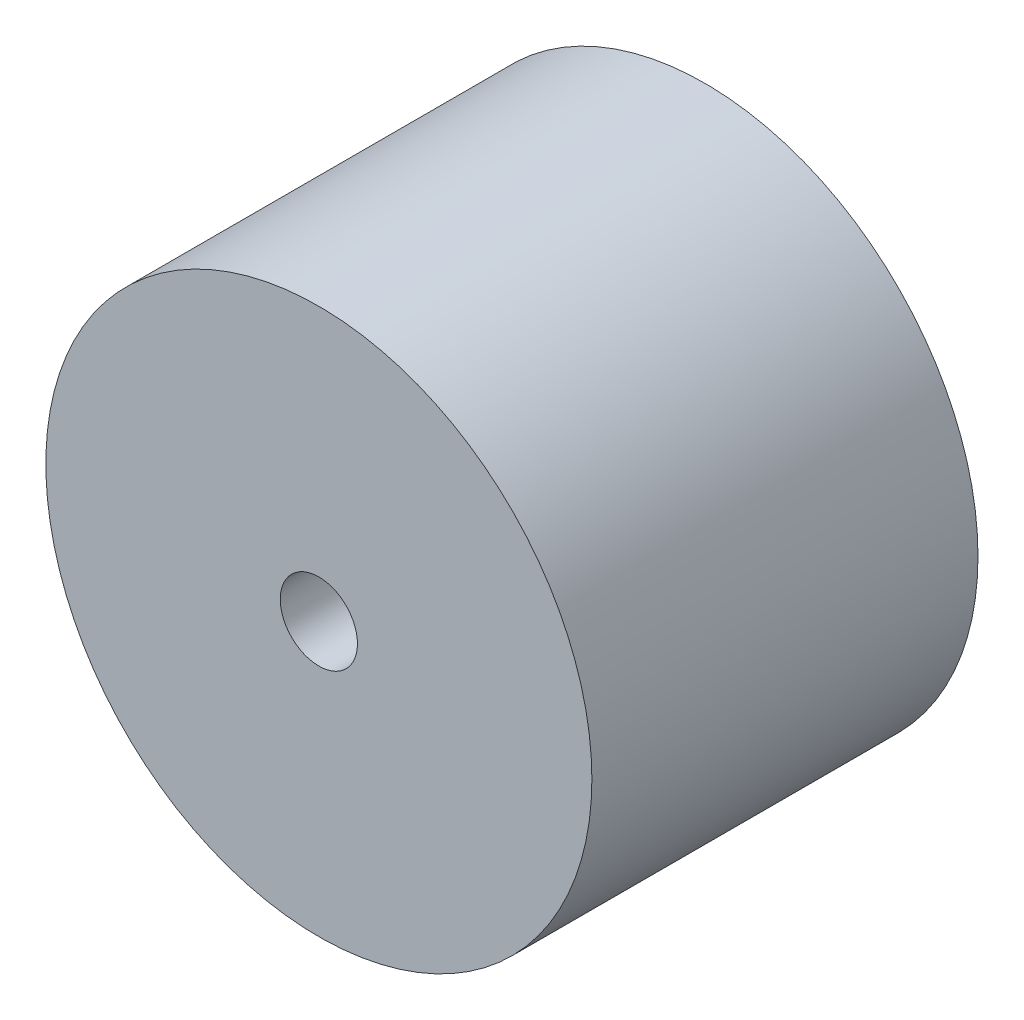
SolidWorks part; units mm, degrees
ref_plane "正面" through (0, 0, 0) normal (0, 0, 1) x (1, 0, 0)
ref_plane "平面" through (0, 0, 0) normal (0, 1, 0) x (1, 0, 0)
ref_plane "右側面" through (0, 0, 0) normal (1, 0, 0) x (0, 0, -1)
sketch "ｽｹｯﾁ2" plane through (0, 0, 0) normal (0, 0, 1) x (1, 0, 0)
  line L1 (-7.5, 7.5) -> (7.5, 7.5) construction
  line L2 (-7.5, 7.5) -> (-7.5, -7.5) construction
  line L3 (-7.5, -7.5) -> (7.5, -7.5) construction
  line L4 (7.5, 7.5) -> (7.5, -7.5) construction
  line L5 (-7.5, 7.5) -> (7.5, -7.5) construction
  line L6 (-7.5, -7.5) -> (7.5, 7.5) construction
  circle A0 centre (0, 0) radius 10.6066
  circle A1 centre (0, 0) radius 1.5
  dimension "D1" = 15
  dimension "D3" = 3
  dimension "D2" = 15
extrude "ﾎﾞｽ - 押し出し1" add sketch "ｽｹｯﾁ2" along normal blind 15
